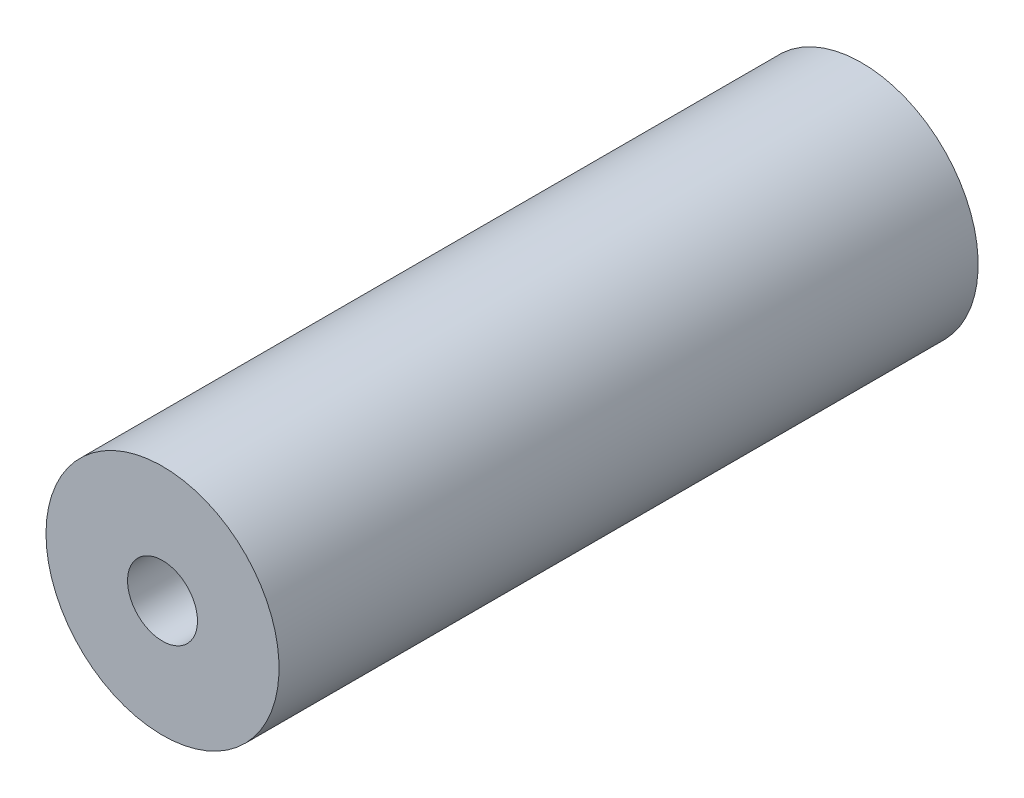
SolidWorks part; units mm, degrees
ref_plane "Front Plane" through (0, 0, 0) normal (0, 0, 1) x (1, 0, 0)
ref_plane "Top Plane" through (0, 0, 0) normal (0, 1, 0) x (1, 0, 0)
ref_plane "Right Plane" through (0, 0, 0) normal (1, 0, 0) x (0, 0, -1)
sketch "Sketch2" plane through (0, 0, 0) normal (0, 0, 1) x (1, 0, 0)
  circle A0 centre (0, 0) radius 3.5
extrude "Boss-Extrude1" add sketch "Sketch2" along normal blind 21
sketch "Sketch4" plane through (0, 0, 0) normal (0, 0, -1) x (-1, 0, 0)
  line L1 (-2.325, 2.325) -> (2.325, 2.325)
  line L2 (-2.325, 2.325) -> (-2.325, -2.325)
  line L3 (-2.325, -2.325) -> (2.325, -2.325)
  line L4 (2.325, 2.325) -> (2.325, -2.325)
  line L5 (-2.325, 2.325) -> (2.325, -2.325) construction
  line L6 (-2.325, -2.325) -> (2.325, 2.325) construction
  point P0 (0, 0)
  dimension "D1" = 4.65
  dimension "D2" = 4.65
sketch "Sketch7" plane through (0, 0, 21) normal (0, 0, 1) x (1, 0, 0)
  circle A0 centre (0, 0) radius 1.05
extrude "Cut-Extrude2" cut sketch "Sketch7" against normal blind 6
extrude "Cut-Extrude5" cut sketch "Sketch4" against normal blind 10.2
ref_plane "Plane1" through (0, 0, 11.5) normal (0, 0, -1) x (-1, 0, 0)
sketch "Sketch14" plane through (0, 0, 11.5) normal (0, 0, -1) x (-1, 0, 0)
  circle A0 centre (0, 0) radius 3.5
